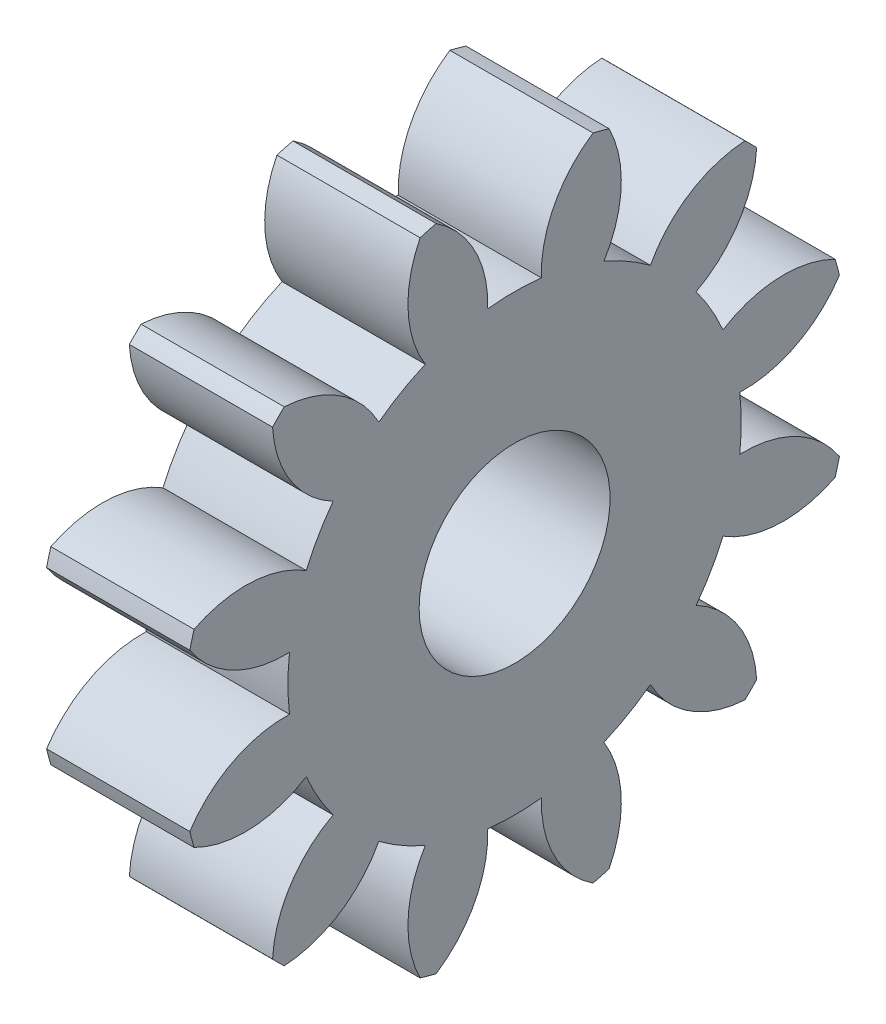
SolidWorks part; units mm, degrees
ref_plane "Plane1" through (0, 0, 0) normal (0, 0, 1) x (1, 0, 0)
ref_plane "Plane2" through (0, 0, 0) normal (0, 1, 0) x (1, 0, 0)
ref_plane "Plane3" through (0, 0, 0) normal (1, 0, 0) x (0, 0, -1)
sketch "HoldingSke" plane through (0, 0, 0) normal (0, 1, 0) x (1, 0, 0)
  line L0 (0, 0) -> (0.9781, -0.2079)
  line L1 (-15, 0) -> (100, 0) construction
  line L2 (0, 0) -> (-2.1039, 2.3779)
  line L3 (0, 0) -> (-11.863, 4.5341)
  line L4 (0, 0) -> (8.4473, 1.7955)
  line L5 (0, 0) -> (-46.8476, -17.4728)
  line L6 (0, 0) -> (-9.9476, -6.7116)
  line L7 (-2.1039, 2.3779) -> (8.6586, 51.2059)
  line L8 (-76.2, 54.61) -> (-75.5, 54.61)
  line L9 (-71.009, 38.7566) -> (-53.1078, 45.2721)
  line L10 (-76.2, 71.12) -> (104.1128, 71.12)
  line L11 (0, 0) -> (-12, 0)
  line L12 (-76.2, 101.6) -> (-76.162, 101.6)
  line L13 (24.9733, 27.94) -> (52.9518, 28.4284)
  line L14 (24.9733, 27.94) -> (24.9743, 27.94)
  line L15 (24.9733, 27.94) -> (100.4006, 29.5858)
  line L16 (-63.627, -1) -> (-12.827, -1)
  circle A0 centre (0, 0) radius 2
  circle A1 centre (0, 0) radius 4.749
  circle A2 centre (0, 0) radius 37.5
  circle A3 centre (0, 0) radius 2
  dimension "MHD" = 9.498
  dimension "Hub_dia" = 75
  dimension "Bore" = 4
  dimension "MBD" = 4
  dimension "Num_teeth" = 12
  dimension "Pitch" = 1
  dimension "Overall_len" = 50
  dimension "Show_teeth" = 12
  dimension "Thickness" = 12
  dimension "OAL" = 50.0001
  dimension "T_dim" = 0.7
  dimension "Ap" = 20
  dimension "H" = 19.05
  dimension "Pitch_radius" = 180.3128
  dimension "Width" = 12
  dimension "Backlash" = 0.038
  dimension "Addendum_fac" = 1
  dimension "Dedendum_fac" = 1.25
  dimension "Clearance_fac" = 0.25
  dimension "Dedendum_add" = 0.001
  dimension "Module" = 1
sketch "BasProSke" plane through (0, 0, 0) normal (0, 1, 0) x (1, 0, 0)
  line L0 (-10, 0) -> (60, 0) construction
  line L1 (0, 0) -> (0, 7)
  line L2 (0, 0) -> (12, 0)
  line L3 (12, 0) -> (12, 7)
  line L4 (12, 7) -> (0, 7)
  dimension "Thickness" = 12
  dimension "Diameter" = 14
revolve "Base-Revolve" add sketch "BasProSke" angle 360 about L0
sketch "TooCutSke" plane through (0, 0, 0) normal (1, 0, 0) x (0, 0, -1)
  line L1 (0, 0) -> (0, 107) construction
  line L2 (0, 0) -> (-0.8496, 5.9395) construction
  line L3 (0, 0) -> (-3.0836, 11.5081) construction
  line L4 (-0.8496, 5.9395) -> (-1.5418, 5.7541) construction
  arc A0 (0.5622, 4.7156) -> (-0.5622, 4.7156) centre (0, 0) ccw
  arc A1 (1.6729, 6.8233) -> (-1.6729, 6.8233) centre (0, 0) ccw
  circle A2 centre (0, 0) radius 6 construction
  circle A3 centre (0, 0) radius 5.6382 construction
  arc A4 (-0.5622, 4.7156) -> (-1.6729, 6.8233) centre (-2.9608, 4.7982) ccw
  arc A5 (1.6729, 6.8233) -> (0.5622, 4.7156) centre (2.9608, 4.7982) ccw
  dimension "Root_dia" = 9.498
  dimension "Overcut_dia" = 14.0508
  dimension "Pitch_dia" = 12
  dimension "Base_dia" = 11.2763
  dimension "Flank_rad" = 2.4
  dimension "Half_ang" = 15
  dimension "Half_CT" = 0.7167
extrude "ToothCut" cut sketch "TooCutSke" along normal through all
fillet "Breaks" [suppressed] radius 0.02
fillet "RootFillets" [suppressed] radius 0.251
pattern_circular "TeethCuts" count 12 every 30 about axis through (-10, 0, 0) along (1, 0, 0) of "ToothCut", "RootFillets", "Breaks"
sketch "HubNeaOneSke" plane through (0, 0, 0) normal (-1, 0, 0) x (0, 0, 1)
  circle A0 centre (0, 0) radius 4.749
  dimension "Diameter" = 9.498
extrude "HubNearOne" [suppressed] add sketch "HubNeaOneSke" along normal blind 38.0001
sketch "HubNeaBotSke" plane through (0, 0, 0) normal (-1, 0, 0) x (0, 0, 1)
  circle A0 centre (0, 0) radius 4.749
  dimension "Diameter" = 9.498
extrude "HubNearBoth" [suppressed] add sketch "HubNeaBotSke" along normal blind 19
ref_plane "FarPln" through (12, 0, 0) normal (1, 0, 0) x (0, 0, -1)
sketch "HubFarSke" plane through (12, 0, 0) normal (1, 0, 0) x (0, 0, -1)
  circle A0 centre (0, 0) radius 4.749
  dimension "Diameter" = 9.498
extrude "HubFar" [suppressed] add sketch "HubFarSke" along normal blind 19
sketch "BorSke" plane through (0, 0, 0) normal (1, 0, 0) x (0, 0, -1)
  circle A0 centre (0, 0) radius 2
  dimension "Diameter" = 4
extrude "Bore" cut sketch "BorSke" along normal mid plane 100.0001
sketch "KeySke" plane through (0, 0, 0) normal (1, 0, 0) x (0, 0, -1)
  line L0 (-0.8, 0) -> (-0.8, 2.7)
  line L1 (-0.8, 2.7) -> (0.8, 2.7)
  line L2 (0.8, 2.7) -> (0.8, 0)
  line L3 (0, 0) -> (0, 34) construction
  line L4 (-0.8, 0) -> (0.8, 0)
  dimension "Offset" = 2.7
  dimension "Width" = 1.6
extrude "Keyway" [suppressed] cut sketch "KeySke" along normal mid plane 100.0001
pattern_circular "Keyway2" [suppressed] count 2 every 90 about axis through (-10, 0, 0) along (1, 0, 0)
sketch "Croquis1" plane through (0, 0, 0) normal (-1, 0, 0) x (0, 0, 1)
  line L1 (-7.7457, 7.7432) -> (7.5999, 7.7432)
  line L2 (-7.7457, 7.7432) -> (-7.7457, -7.6367)
  line L3 (-7.7457, -7.6367) -> (7.5999, -7.6367)
  line L4 (7.5999, 7.7432) -> (7.5999, -7.6367)
extrude "Cortar-Extruir1" cut sketch "Croquis1" against normal blind 9
equation "' \"Module@HoldingSke\" = 6.35"
equation "' \"Num_teeth@HoldingSke\" = 12"
equation "' \"Ap@HoldingSke\" =  20"
equation "' \"Ap@HoldingSke\" = 20"
equation "' \"Width@HoldingSke\" = 0.5 * 25.4"
equation "' \"Hub_dia@HoldingSke\"= 1 * 25.4"
equation "' \"Hub_dia@HoldingSke\" = 1 * 25.4"
equation "' \"Overall_len@HoldingSke\" = 1.0 * 25.4"
equation "' \"Bore@HoldingSke\" = 0.75 * 25.4"
equation "' \"T_dim@HoldingSke\" = 0.1 * 25.4"
equation "' \"Width@KeySke\" = 0.25 * 25.4"
equation "' \"Show_teeth@HoldingSke\" = 13"
equation "' \"Backlash@HoldingSke\" = 0.009 * 25.4"
equation "' \"Addendum_fac@HoldingSke\" = 1.0"
equation "' \"Dedendum_fac@HoldingSke\" = 1.25"
equation "' \"Dedendum_add@HoldingSke\" = 0.00005 * 25.4"
equation "' \"Clearance_fac@HoldingSke\" = 0.25"
equation "\"Pitch@HoldingSke\" = 1 / \"Module@HoldingSke\""
equation "\"Overcut_dia@TooCutSke\" = (\"Num_teeth@HoldingSke\" + 2 * \"Addendum_fac@HoldingSke\") / \"Pitch@HoldingSke\" + 0.002 * 25.4"
equation "\"Pitch_dia@TooCutSke\" = \"Num_teeth@HoldingSke\" / \"Pitch@HoldingSke\""
equation "\"Base_dia@TooCutSke\" = \"Num_teeth@HoldingSke\" / \"Pitch@HoldingSke\" * cos((\"Ap@HoldingSke\"  * 3.14159265 / 180))"
equation "\"Root_dia@TooCutSke\" = (\"Num_teeth@HoldingSke\" + 2) / \"Pitch@HoldingSke\" - 2 * (\"Addendum_fac@HoldingSke\" + \"Dedendum_fac@HoldingSke\") / \"Pitch@HoldingSke\" - \"Dedendum_add@HoldingSke\" * 2"
equation "\"Half_ang@TooCutSke\" = 180 / \"Num_teeth@HoldingSke\""
equation "\"Half_CT@TooCutSke\" = \"Num_teeth@HoldingSke\" / \"Pitch@HoldingSke\" * sin((3.14159265 / 2 / \"Num_teeth@HoldingSke\")) / 2 - 7 * \"Backlash@HoldingSke\" / 4"
equation "\"Flank_rad@TooCutSke\" = \"Num_teeth@HoldingSke\" / \"Pitch@HoldingSke\" / 5"
equation "\"Radius@RootFillets\" = \"Clearance_fac@HoldingSke\" / \"Pitch@HoldingSke\" + \"Dedendum_add@HoldingSke\""
equation "\"Break_rad@Breaks\" = 0.02 / \"Pitch@HoldingSke\""
equation "\"Thickness@HoldingSke\" = \"Width@HoldingSke\""
equation "\"OAL@HoldingSke\" = \"Thickness@HoldingSke\""
equation "\"MHD@HoldingSke\" = (\"Num_teeth@HoldingSke\" + 2) / \"Pitch@HoldingSke\" - 2 * (\"Addendum_fac@HoldingSke\" + \"Dedendum_fac@HoldingSke\")  / \"Pitch@HoldingSke\" - \"Dedendum_add@HoldingSke\" * 2"
equation "\"MBD@HoldingSke\" = (\"Num_teeth@HoldingSke\" + 2) / \"Pitch@HoldingSke\" - 2 * (\"Addendum_fac@HoldingSke\" + \"Dedendum_fac@HoldingSke\")  / \"Pitch@HoldingSke\" - \"Dedendum_add@HoldingSke\" * 2 - 0.002 * 25.4"
equation "\"MHD@HoldingSke\" = ((sgn( \"MHD@HoldingSke\" - \"Hub_dia@HoldingSke\" )-1)*( \"MHD@HoldingSke\" - \"Hub_dia@HoldingSke\" ))/-2+ \"Hub_dia@HoldingSke\""
equation "\"MBD@HoldingSke\" = ((sgn( \"MBD@HoldingSke\" - \"Bore@HoldingSke\" )-1)*( \"MBD@HoldingSke\" - \"Bore@HoldingSke\" ))/-2+ \"Bore@HoldingSke\""
equation "\"OAL@HoldingSke\" = ((sgn( \"OAL@HoldingSke\" - \"Overall_len@HoldingSke\" )+1)*( \"OAL@HoldingSke\" - \"Overall_len@HoldingSke\" ))/2 + \"Overall_len@HoldingSke\" + 0.000002 * 25.4"
equation "\"Num_teeth@TeethCuts\" = int( \"Show_teeth@HoldingSke\" ) + 1"
equation "\"Num_teeth@TeethCuts\" = ((sgn( \"Num_teeth@TeethCuts\" - \"Num_teeth@HoldingSke\" )-1)*( \"Num_teeth@TeethCuts\" - \"Num_teeth@HoldingSke\" ))/-2+ \"Num_teeth@HoldingSke\""
equation "\"Num_teeth@TeethCuts\" = ((sgn( \"Num_teeth@TeethCuts\" - 2.0)+1)*( \"Num_teeth@TeethCuts\" - 2.0))/2 +2.0"
equation "\"Angle@TeethCuts\" = 360.0 / \"Num_teeth@HoldingSke\""
equation "\"Diameter@BasProSke\" = (\"Num_teeth@HoldingSke\" + 2 * \"Addendum_fac@HoldingSke\") / \"Pitch@HoldingSke\""
equation "\"Thickness@BasProSke\"  = \"Thickness@HoldingSke\""
equation "' \"Fillet_rad@BasProSke\" =  \"Thickness@HoldingSke\" * 0.05"
equation "' \"Fillet_rad@BasProSke\" = \"Thickness@HoldingSke\" * 0.05"
equation "\"MHD@HoldingSke\" = ((sgn( \"MHD@HoldingSke\" - \"Root_dia@TooCutSke\" )-1)*( \"MHD@HoldingSke\" - \"Root_dia@TooCutSke\" ))/-2+ \"Root_dia@TooCutSke\""
equation "\"Diameter@HubNeaOneSke\" = \"MHD@HoldingSke\""
equation "\"Length@HubNearOne\" = \"OAL@HoldingSke\" - \"Thickness@BasProSke\""
equation "\"Diameter@HubNeaBotSke\" = \"MHD@HoldingSke\""
equation "\"Length@HubNearBoth\" = ( \"OAL@HoldingSke\" - \"Thickness@BasProSke\" ) / 2.0"
equation "\"Thickness@FarPln\" = \"Thickness@BasProSke\""
equation "\"Diameter@HubFarSke\" = \"MHD@HoldingSke\""
equation "\"Length@HubFar\" = ( \"OAL@HoldingSke\" - \"Thickness@BasProSke\" ) / 2.0"
equation "\"Diameter@BorSke\" = \"MBD@HoldingSke\""
equation "\"D1@Bore\" = \"OAL@HoldingSke\" * 2.0"
equation "\"D1@Keyway\" = \"OAL@HoldingSke\" * 2.0"
equation "\"Offset@KeySke\" = \"T_dim@HoldingSke\" + \"MBD@HoldingSke\" / 2.0"
